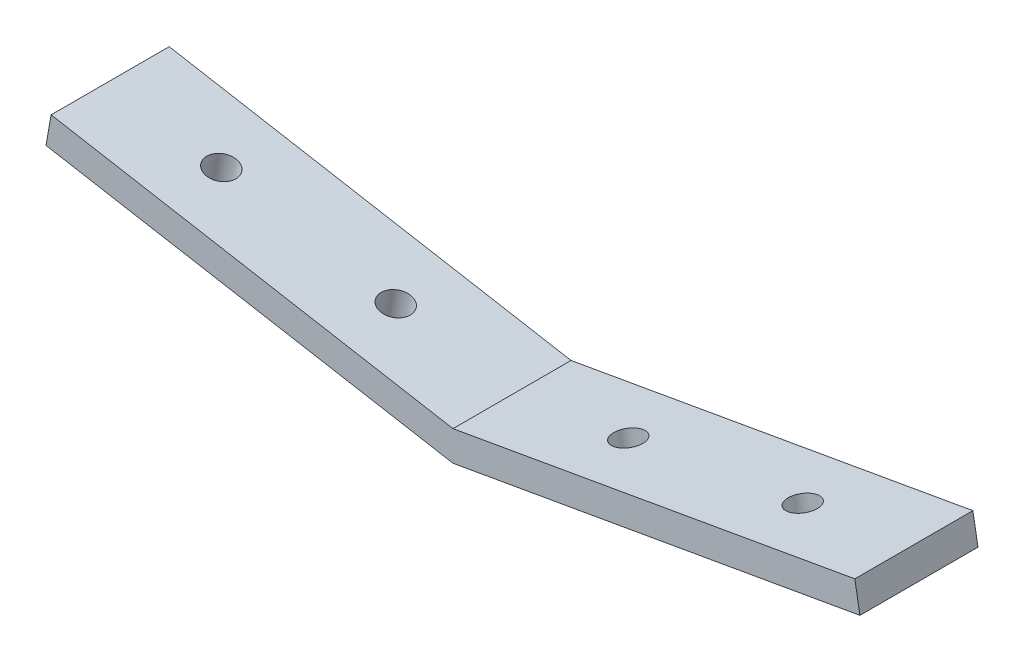
SolidWorks part; units mm, degrees
material "ABS"
ref_plane "前视基准面" through (0, 0, 0) normal (0, 0, 1) x (1, 0, 0)
ref_plane "上视基准面" through (0, 0, 0) normal (0, 1, 0) x (1, 0, 0)
ref_plane "右视基准面" through (0, 0, 0) normal (1, 0, 0) x (0, 0, -1)
sketch "草图1" plane through (0, 0, 0) normal (0, 0, 1) x (1, 0, 0)
  line L0 (-92.3155, 0) -> (92.3155, 0) construction
  line L5 (0, -55) -> (0, 55) construction
  line L6 (0, 0) -> (-137.8731, 24.3107)
  line L8 (0, 0) -> (137.8731, 24.3107)
  line L9 (-137.8731, 24.3107) -> (-136.1366, 34.1588)
  line L10 (-136.1366, 34.1588) -> (0, 10.1543)
  line L11 (136.1366, 34.1588) -> (0, 10.1543)
  line L12 (137.8731, 24.3107) -> (136.1366, 34.1588)
  point P0 (0, 0)
extrude "凸台-拉伸1" add sketch "草图1" along normal blind 40
sketch "草图2" plane through (1.7365, 9.8481, 0) normal (0.1736, 0.9848, 0) x (0.9848, -0.1736, 0)
  line L0 (-1.7633, -40) -> (-1.7633, 0) construction
  line L1 (-1.7633, 0) -> (-140, 0) construction
  circle A0 centre (-41.7633, -20) radius 5
  circle A1 centre (-101.7633, -20) radius 5
  point P6 (0, 0)
  dimension "D1" = 40
  dimension "D2" = 60
  dimension "D3" = 20
extrude "切除-拉伸1" cut sketch "草图2" against normal through all
mirror "镜向1" about plane through (0, 0, 0) normal (1, 0, 0) of "切除-拉伸1"
